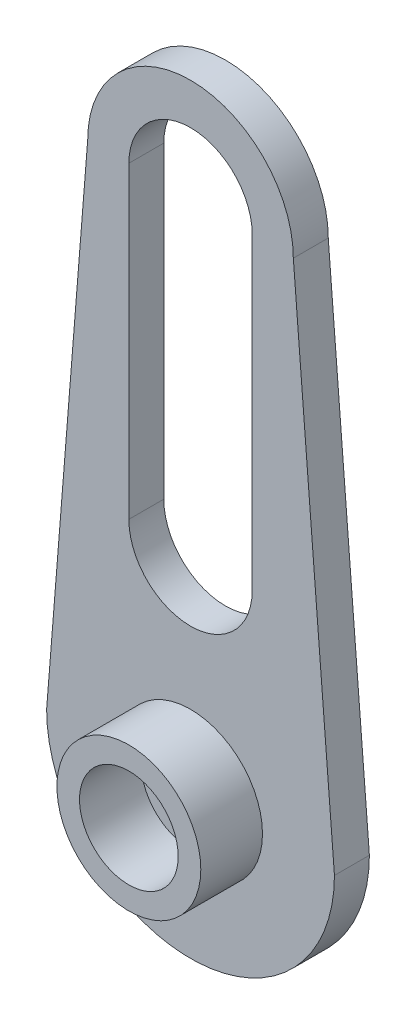
SolidWorks part; units mm, degrees
ref_plane "Alzado" through (0, 0, 0) normal (0, 0, 1) x (1, 0, 0)
ref_plane "Planta" through (0, 0, 0) normal (0, 1, 0) x (1, 0, 0)
ref_plane "Vista lateral" through (0, 0, 0) normal (1, 0, 0) x (0, 0, -1)
sketch "Croquis1" plane through (0, 0, 0) normal (0, 0, 1) x (1, 0, 0)
  line L0 (0, 0) -> (0, 25) construction
  line L1 (-5, 25) -> (-7, 0)
  line L2 (5, 25) -> (7, 0)
  line L3 (3, 25) -> (3, 10)
  line L4 (-3, 10) -> (-3, 25)
  arc A0 (-6.911, 1.1129) -> (6.911, 1.1129) centre (0, 0) ccw
  arc A1 (5, 25) -> (-5, 25) centre (0, 25) ccw
  circle A2 centre (0, 0) radius 1.1
  arc A3 (3, 25) -> (-3, 25) centre (0, 25) ccw
  arc A4 (-3, 10) -> (3, 10) centre (0, 10) ccw
  point P14 (0, 0)
  dimension "D1" = 14
  dimension "D2" = 10
  dimension "D4" = 2.2
  dimension "D5" = 3
  dimension "D6" = 3
  dimension "D3" = 25
  dimension "D7" = 15
extrude "Saliente-Extruir1" add sketch "Croquis1" along normal blind 1.7
sketch "Croquis2" plane through (0, 0, 1.7) normal (0, 0, 1) x (1, 0, 0)
  circle A0 centre (0, 0) radius 3.5
  circle A1 centre (0, 0) radius 2.4
  dimension "D1" = 1.1
  dimension "D2" = 7
extrude "Saliente-Extruir2" add sketch "Croquis2" along normal blind 3
sketch "Croquis3" plane through (0, 0, 0) normal (0, 0, -1) x (-1, 0, 0)
  circle A0 centre (0, 0) radius 2.25
  dimension "D1" = 4.5
extrude "Cortar-Extruir1" cut sketch "Croquis3" against normal blind 1
